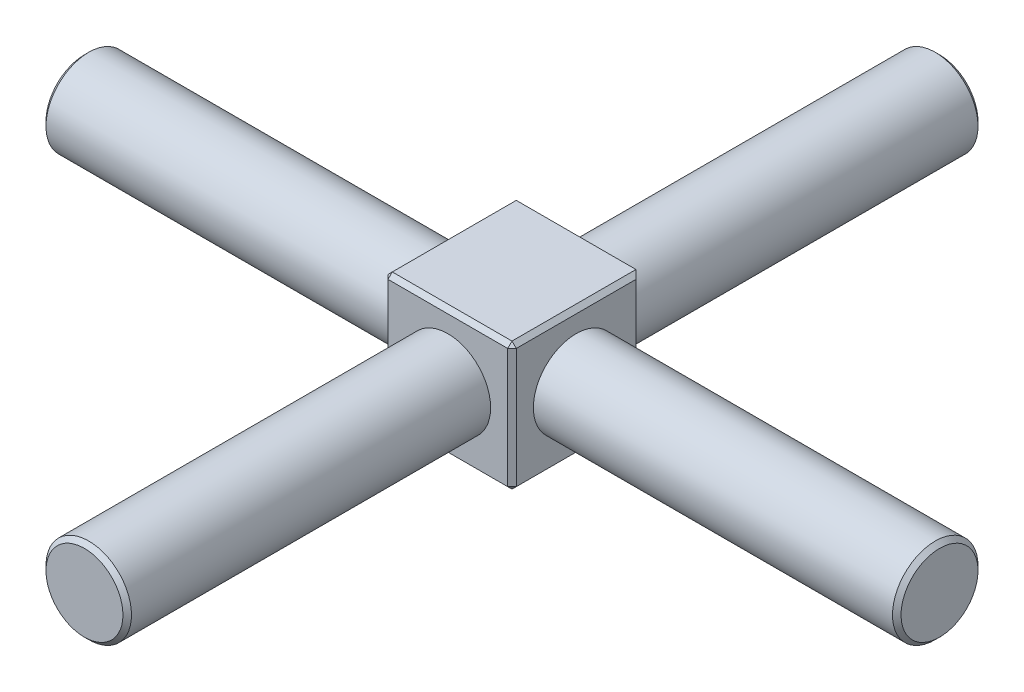
SolidWorks part; units mm, degrees
ref_plane "Front Plane" through (0, 0, 0) normal (0, 0, 1) x (1, 0, 0)
ref_plane "Top Plane" through (0, 0, 0) normal (0, 1, 0) x (1, 0, 0)
ref_plane "Right Plane" through (0, 0, 0) normal (1, 0, 0) x (0, 0, -1)
sketch "Sketch1" plane through (0, 0, 0) normal (0, 0, 1) x (1, 0, 0)
  line L1 (-7.5, 7.5) -> (7.5, 7.5)
  line L2 (-7.5, 7.5) -> (-7.5, -7.5)
  line L3 (-7.5, -7.5) -> (7.5, -7.5)
  line L4 (7.5, 7.5) -> (7.5, -7.5)
  line L5 (-7.5, 7.5) -> (7.5, -7.5) construction
  line L6 (-7.5, -7.5) -> (7.5, 7.5) construction
  point P0 (0, 0)
  dimension "D1" = 15
  dimension "D2" = 15
extrude "Boss-Extrude1" add sketch "Sketch1" along normal blind 15
sketch "Sketch3" plane through (7.5, 0, 0) normal (1, 0, 0) x (0, 0, -1)
  circle A0 centre (-7.5, 0) radius 5
  dimension "D1" = 10
  dimension "D2" = 7.5
extrude "Boss-Extrude2" add sketch "Sketch3" along normal mid plane 100 from offset 7.5 offset against normal yes
sketch "Sketch4" plane through (0, 0, 15) normal (0, 0, 1) x (1, 0, 0)
  circle A0 centre (0, 0) radius 5
  dimension "D1" = 10
extrude "Boss-Extrude3" add sketch "Sketch4" along normal mid plane 100 from offset 7.5 offset against normal yes
chamfer "Chamfer1" distance 0.5 angle 45 15 edges at (50, 5, 7.5) (5, 0, -42.5) (-50, 5, 7.5) (5, 0, 57.5) (-7.5, 7.5, 7.5) (-7.5, 0, 15) (-7.5, -7.5, 7.5) (-7.5, 0, 0) (0, -7.5, 0) (7.5, 7.5, 7.5) (7.5, 0, 0) (7.5, -7.5, 7.5) (0, -7.5, 15) (7.5, 0, 15) (0, 7.5, 15)
